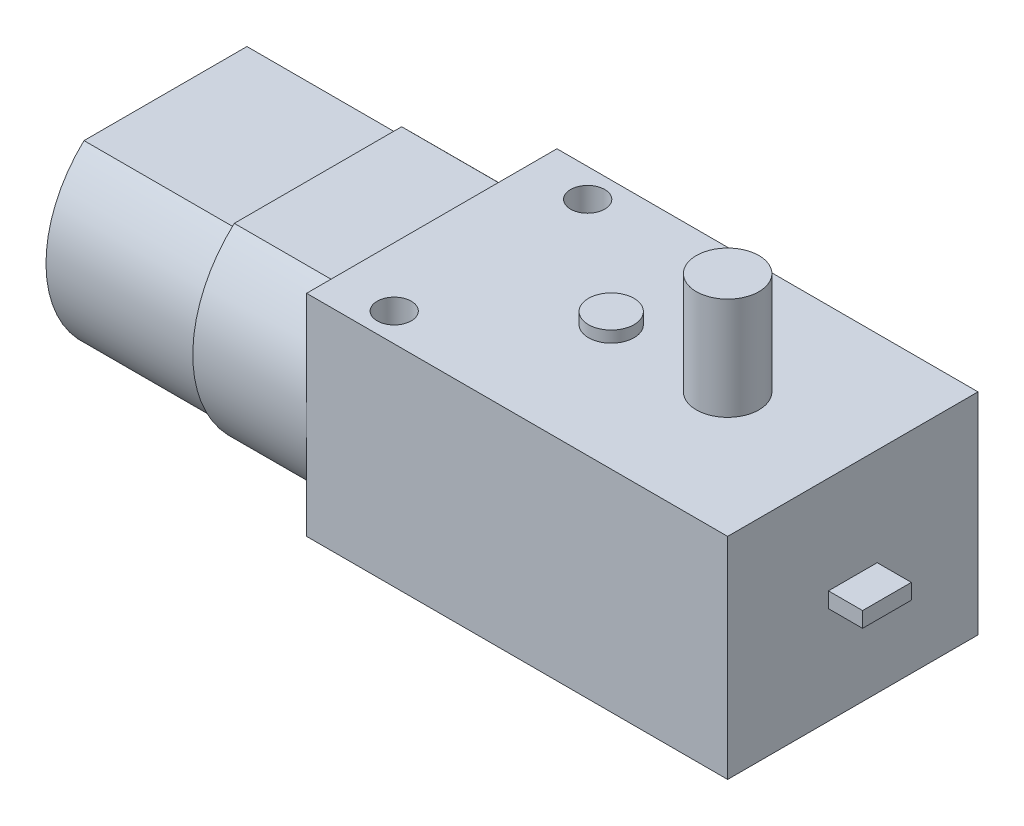
SolidWorks part; units mm, degrees
ref_plane "정면" through (0, 0, 0) normal (0, 0, 1) x (1, 0, 0)
ref_plane "윗면" through (0, 0, 0) normal (0, 1, 0) x (1, 0, 0)
ref_plane "우측면" through (0, 0, 0) normal (1, 0, 0) x (0, 0, -1)
sketch "스케치1" plane through (0, 0, 0) normal (0, 0, 1) x (1, 0, 0)
  line L0 (-18.5, 9.25) -> (-18.5, -9.25)
  line L1 (-18.5, 9.25) -> (18.5, 9.25)
  line L3 (-18.5, -9.25) -> (18.5, -9.25)
  line L4 (18.5, 9.25) -> (18.5, -9.25)
  point P8 (18.5, 0)
  point P9 (0, 9.25)
  dimension "D1" = 18.5
  dimension "D2" = 37
extrude "보스-돌출1" add sketch "스케치1" along normal mid plane 22
sketch "스케치2" plane through (-18.5, 0, 0) normal (-1, 0, 0) x (0, 0, 1)
  line L0 (-6.2252, -9.5) -> (6.2252, -9.5)
  line L5 (-7.3533, 7.75) -> (7.3533, 7.75)
  line L8 (11, 9.25) -> (-11, 9.25) construction
  arc A0 (6.2252, -9.5) -> (7.3533, 7.75) centre (0, -0.431) ccw
  arc A1 (-7.3533, 7.75) -> (-6.2252, -9.5) centre (0, -0.431) ccw
  dimension "D1" = 1.5
  dimension "D2" = 11
extrude "보스-돌출2" add sketch "스케치2" along normal blind 10
sketch "스케치3" plane through (-28.5, 0, 0) normal (-1, 0, 0) x (0, 0, 1)
  line L4 (-6.0681, -9) -> (6.0681, -9)
  line L5 (7.1591, 7.25) -> (-7.1591, 7.25)
  line L6 (-6.0681, -9) -> (6.0681, -9)
  line L7 (7.1591, 7.25) -> (-7.1591, 7.25)
  arc A4 (-7.1591, 7.25) -> (-6.0681, -9) centre (0, -0.431) ccw
  arc A5 (6.0681, -9) -> (7.1591, 7.25) centre (0, -0.431) ccw
  arc A6 (-7.1591, 7.25) -> (-6.0681, -9) centre (0, -0.431) ccw
  arc A7 (6.0681, -9) -> (7.1591, 7.25) centre (0, -0.431) ccw
  dimension "D1" = 0.5
extrude "보스-돌출3" add sketch "스케치3" along normal blind 13.4
sketch "스케치4" plane through (18.5, 0, 0) normal (1, 0, 0) x (0, 0, -1)
  line L1 (2.1427, 0.6773) -> (-2.1427, 0.6773)
  line L2 (2.1427, 0.6773) -> (2.1427, -0.6773)
  line L3 (2.1427, -0.6773) -> (-2.1427, -0.6773)
  line L4 (-2.1427, 0.6773) -> (-2.1427, -0.6773)
  line L5 (2.1427, 0.6773) -> (-2.1427, -0.6773) construction
  line L6 (2.1427, -0.6773) -> (-2.1427, 0.6773) construction
  point P0 (0, 0)
extrude "보스-돌출4" add sketch "스케치4" along normal blind 3
sketch "스케치5" plane through (0, 9.25, 0) normal (0, 1, 0) x (1, 0, 0)
  line L0 (-16, 0) -> (18.5, 0) construction
  line L2 (18.5, 2.1427) -> (18.5, -2.1427) construction
  circle A0 centre (-2.729, 0) radius 2
  dimension "D1" = 4
extrude "보스-돌출5" add sketch "스케치5" along normal blind 1
sketch "스케치6" plane through (0, 9.25, 0) normal (0, 1, 0) x (1, 0, 0)
  line L0 (-18.5, 8.5) -> (18.5, 8.5) construction
  line L1 (-18.5, 11) -> (-18.5, 7.3533) construction
  line L2 (18.5, -11) -> (18.5, 11) construction
  line L3 (-13.3, 11) -> (-13.3, -11) construction
  line L4 (18.5, 11) -> (-18.5, 11) construction
  line L5 (18.5, -11) -> (-18.5, -11) construction
  line L6 (-16, 0) -> (18.5, 0) construction
  circle A0 centre (-13.3, 8.5) radius 1.5
  circle A1 centre (-13.3, -8.5) radius 1.5
  point P12 (-13.3, 8.5)
  point P21 (-13.3, 10)
  point P22 (-14.8, 8.5)
  dimension "D1" = 3
  dimension "D2" = 3.7
  dimension "D3" = 1
extrude "컷-돌출1" cut sketch "스케치6" against normal blind 20
sketch "스케치8" plane through (0, 9.25, 0) normal (0, 1, 0) x (1, 0, 0)
  line L0 (18.5, -11) -> (18.5, 11) construction
  circle A0 centre (7.5, 0) radius 2.75
  dimension "D1" = 5.5
  dimension "D2" = 11
extrude "보스-돌출6" add sketch "스케치8" along normal blind 9
